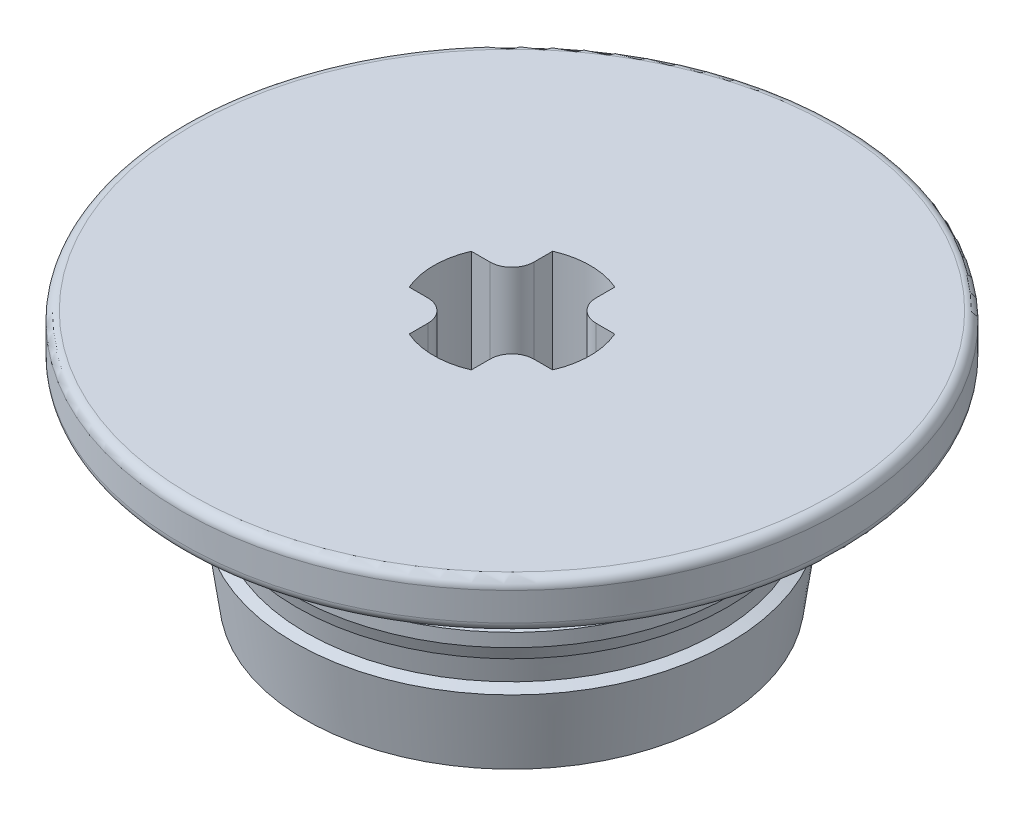
SolidWorks part; units mm, degrees
ref_plane "Front Plane" through (0, 0, 0) normal (0, 0, 1) x (1, 0, 0)
ref_plane "Top Plane" through (0, 0, 0) normal (0, 1, 0) x (1, 0, 0)
ref_plane "Right Plane" through (0, 0, 0) normal (1, 0, 0) x (0, 0, -1)
sketch "Sketch1" plane through (0, 0, 0) normal (0, 1, 0) x (1, 0, 0)
  line L2 (0, 0) -> (0, 47.5777) construction
  line L3 (0, 0) -> (50000, 0) construction
  line L6 (-0.89, 0.89) -> (0, 0) construction
  line L7 (0, 0) -> (0.89, 0.89) construction
  line L12 (2.39, 0) -> (2.39, 3.5727) construction
  line L13 (0, 2.39) -> (50000, 2.39) construction
  line L14 (-2.39, 0.4111) -> (-2.39, -49999.5889) construction
  line L15 (0.2318, -2.39) -> (-49999.7682, -2.39) construction
  line L16 (0, 0) -> (-0.89, -0.89) construction
  line L17 (0, 0) -> (0.89, -0.89) construction
  line L18 (-0.99, 0.99) -> (-2.2847, 0.99)
  line L19 (-2.2847, -0.99) -> (-0.99, -0.99)
  line L20 (-0.99, -0.99) -> (-0.99, -2.2847)
  line L21 (0.99, -2.2847) -> (0.99, -0.99)
  line L22 (0.99, -0.99) -> (2.2842, -0.99)
  line L23 (0.99, 0.99) -> (2.2842, 0.99)
  line L24 (0.99, 2.2875) -> (0.99, 0.99)
  line L25 (-0.99, 2.2875) -> (-0.99, 0.99)
  arc A4 (-2.2847, 0.99) -> (-2.2847, -0.99) centre (0, 0) ccw
  arc A5 (-0.99, -2.2847) -> (0.99, -2.2847) centre (0, 0) ccw
  arc A6 (2.2842, 0.99) -> (2.2842, -0.99) centre (0, 0) cw
  arc A7 (-0.99, 2.2875) -> (0.99, 2.2875) centre (0, 0) cw
  point P0 (0, 0)
  point P15 (0, 2.39)
  point P24 (2.39, 0)
  point P29 (-2.39, 0)
  point P30 (0, -2.39)
  line B0 (-0.89, 2.2181) -> (-0.89, 0.89) construction
  line B1 (-0.89, 0.89) -> (-2.2181, 0.89) construction
  line B2 (0.89, 2.2181) -> (0.89, 0.89) construction
  line B3 (0.89, 0.89) -> (2.2181, 0.89) construction
  line B4 (-2.2181, -0.89) -> (-0.89, -0.89) construction
  line B5 (-0.89, -0.89) -> (-0.89, -2.2181) construction
  line B6 (0.89, -2.2181) -> (0.89, -0.89) construction
  line B7 (0.89, -0.89) -> (2.2181, -0.89) construction
  arc B8 (-0.89, 2.2181) -> (0.89, 2.2181) centre (0, 0) cw construction
  arc B9 (-2.2181, 0.89) -> (-2.2181, -0.89) centre (0, 0) ccw construction
  arc B10 (2.2181, 0.89) -> (2.2181, -0.89) centre (0, 0) cw construction
  arc B11 (-0.89, -2.2181) -> (0.89, -2.2181) centre (0, 0) ccw construction
sketch_block_instance "Lego Axle - Unfilleted-1"
sketch_block "Lego Axle - Unfilleted" parameters "D9"=2.44, "D14"=2.4794, "D15"=2.44, "D1"=10.5762, "D2"=12.3972, "D3"=62.5785, "D4"=1.2287, "D5"=12.9019, "D6"=1.0841, "D7"=1.3117, "D8"=1.78, "D10"=1.3117, "D11"=1.3831, "D12"=0.0285, "D13"=1.3442, "D16"=0.0996
sketch "Sketch2" plane through (0, 0, 0) normal (0, 0, 1) x (1, 0, 0)
  line L0 (0, 0) -> (10.5, 0)
  line L1 (200000.2318, 0) -> (-249999.7682, 0) construction
  line L2 (10.5, 0) -> (10.5, -1.5)
  line L3 (10.5, -1.5) -> (7.5, -1.5)
  line L4 (7.5, -1.5) -> (7.2912, -2.9854)
  line L5 (6.5865, -8) -> (0, -8)
  line L6 (0, -8) -> (0, 0)
  line L7 (0, 0) -> (0, 50000) construction
  line L8 (7.2912, -2.9854) -> (6.9427, -2.9364)
  line L9 (6.9427, -2.9364) -> (6.8035, -3.9267)
  line L12 (6.6902, -4.7326) -> (6.5683, -5.6001)
  line L13 (6.5683, -5.6001) -> (6.9065, -5.7228)
  line L15 (6.9065, -5.7228) -> (6.5865, -8)
  line L17 (6.8035, -3.9267) -> (6.9722, -3.9504)
  line L18 (6.9722, -3.9504) -> (6.9722, -4.3743)
  line L19 (6.9722, -4.3743) -> (6.8619, -4.7568)
  line L20 (6.8619, -4.7568) -> (6.6902, -4.7326)
  point P20 (6.5683, -5.6001)
  dimension "D1" = 15
  dimension "D2" = 8
  dimension "D3" = 8
  dimension "D4" = 1.5
  dimension "D5" = 3
  dimension "D8" = 2.25
  dimension "D9" = 1.5
revolve "Revolve1" add sketch "Sketch2" angle 360 about L7
extrude "Cut-Extrude1" cut sketch "Sketch1" against normal through all
fillet "Fillet1" radius 0.7 4 edges at (-0.99, -4, 0.99) (0.99, -4, 0.99) (0.99, -4, -0.99) (-0.99, -4, -0.99)
fillet "Fillet2" radius 0.3 3 edges at (0, 0, -10.5) (0, -1.5, -7.5) (0, -1.5, -10.5)
